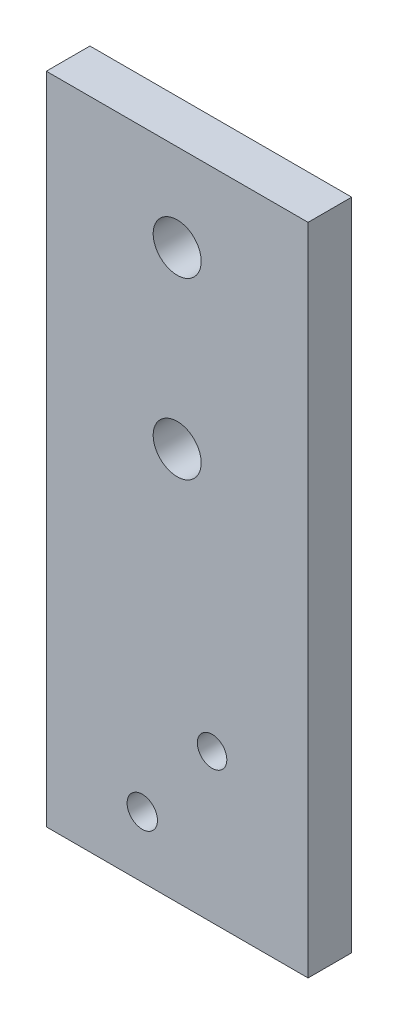
SolidWorks part; units mm, degrees
ref_plane "Plan de face" through (0, 0, 0) normal (0, 0, 1) x (1, 0, 0)
ref_plane "Plan de dessus" through (0, 0, 0) normal (0, 1, 0) x (1, 0, 0)
ref_plane "Plan de droite" through (0, 0, 0) normal (1, 0, 0) x (0, 0, -1)
sketch "Esquisse1" plane through (0, 0, 0) normal (0, 0, 1) x (1, 0, 0)
  line L0 (-11, 17) -> (-11, 7) construction
  line L1 (0, 0) -> (-30, 0)
  line L2 (0, 0) -> (0, 75)
  line L3 (0, 75) -> (-30, 75)
  line L4 (-30, 0) -> (-30, 75)
  line L5 (-11, 7) -> (-19, 7) construction
  circle A0 centre (-15, 65) radius 2.75
  circle A1 centre (-15, 45) radius 2.75
  circle A2 centre (-19, 7) radius 1.7413
  circle A3 centre (-11, 17) radius 1.6893
  point P10 (-15, 75)
  point P14 (-15, 7)
  point P16 (-15, 0)
  dimension "D1" = 5.5
  dimension "D2" = 10
  dimension "D3" = 20
  dimension "D4" = 45
  dimension "D5" = 7
  dimension "D6" = 10
  dimension "D7" = 8
  dimension "D8" = 30
extrude "Boss.-Extru.1" add sketch "Esquisse1" along normal blind 5
